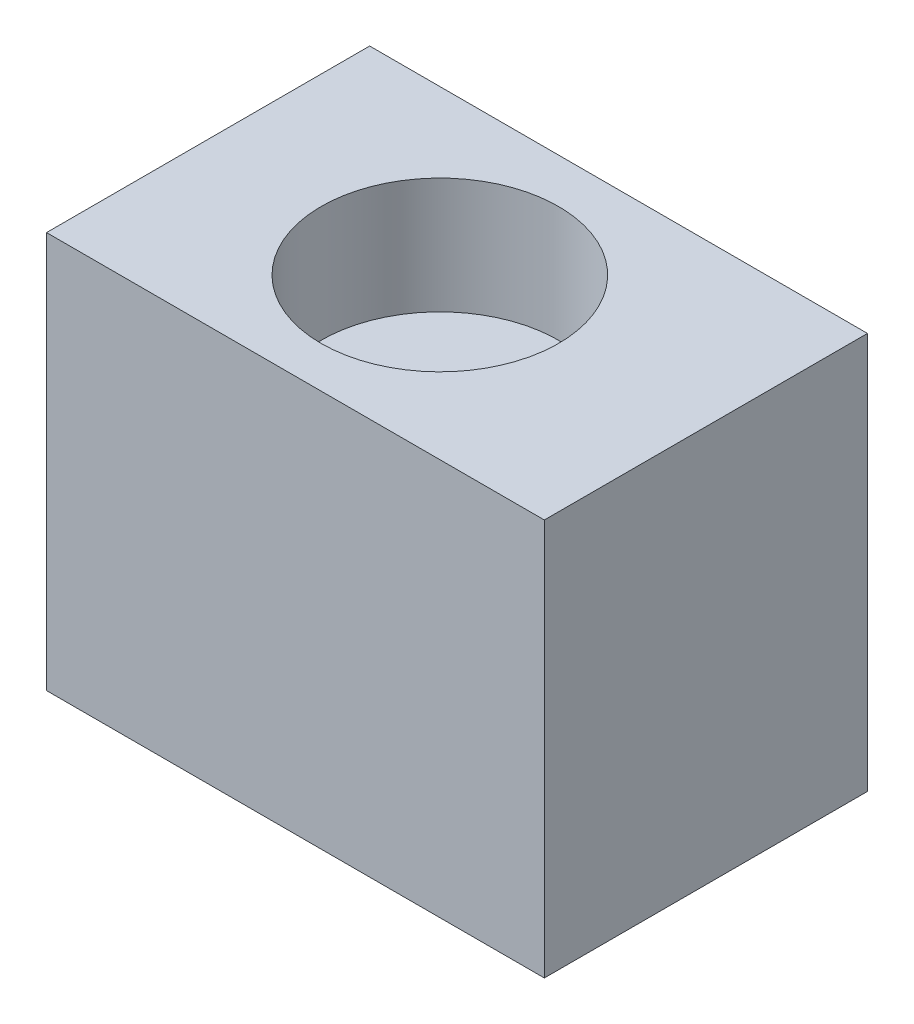
SolidWorks part; units mm, degrees
ref_plane "Plan de face" through (0, 0, 0) normal (0, 0, 1) x (1, 0, 0)
ref_plane "Plan de dessus" through (0, 0, 0) normal (0, 1, 0) x (1, 0, 0)
ref_plane "Plan de droite" through (0, 0, 0) normal (1, 0, 0) x (0, 0, -1)
sketch "Esquisse1" plane through (0, 0, 0) normal (0, 0, 1) x (1, 0, 0)
  line L1 (0, 0) -> (45.97, 0)
  line L2 (0, 0) -> (0, 36.63)
  line L3 (0, 36.63) -> (45.97, 36.63)
  line L4 (45.97, 0) -> (45.97, 36.63)
  dimension "D1" = 36.63
  dimension "D2" = 45.97
extrude "Boss.-Extru.1" add sketch "Esquisse1" along normal blind 29.84
sketch "Esquisse2" plane through (0, 36.63, 0) normal (0, 1, 0) x (1, 0, 0)
  line L0 (45.97, 0) -> (0, 0) construction
  line L1 (45.97, -29.84) -> (45.97, 0) construction
  circle A0 centre (21.55, -15.07) radius 10.96
  dimension "D2" = 21.92
  dimension "D1" = 15.07
  dimension "D3" = 24.42
extrude "Enlèv. mat.-Extru.1" cut sketch "Esquisse2" against normal blind 10.7
equation "\"D1@Esquisse2\"=4.11+\"D2@Esquisse2\"/2"
equation "\"D3@Esquisse2\"=13.46+\"D2@Esquisse2\"/2"
